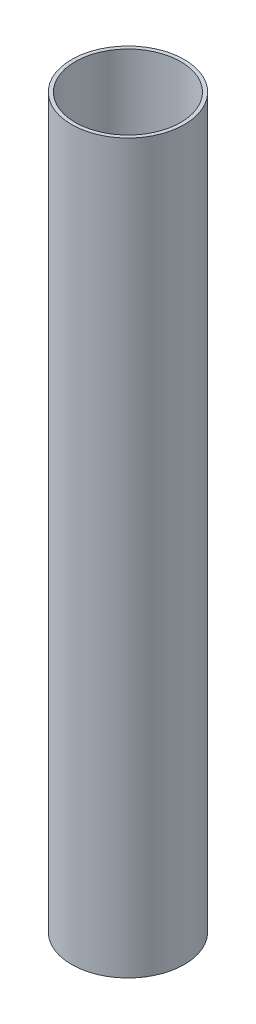
SolidWorks part; units mm, degrees
ref_plane "Front Plane" through (0, 0, 0) normal (0, 0, 1) x (1, 0, 0)
ref_plane "Top Plane" through (0, 0, 0) normal (0, 1, 0) x (1, 0, 0)
ref_plane "Right Plane" through (0, 0, 0) normal (1, 0, 0) x (0, 0, -1)
sketch "Sketch1" plane through (0, 0, 0) normal (0, 1, 0) x (1, 0, 0)
  circle A0 centre (0, 0) radius 14.5
  circle A1 centre (0, 0) radius 15.5
  dimension "D1" = 29
  dimension "D2" = 1
extrude "Boss-Extrude1" add sketch "Sketch1" along normal blind 200
